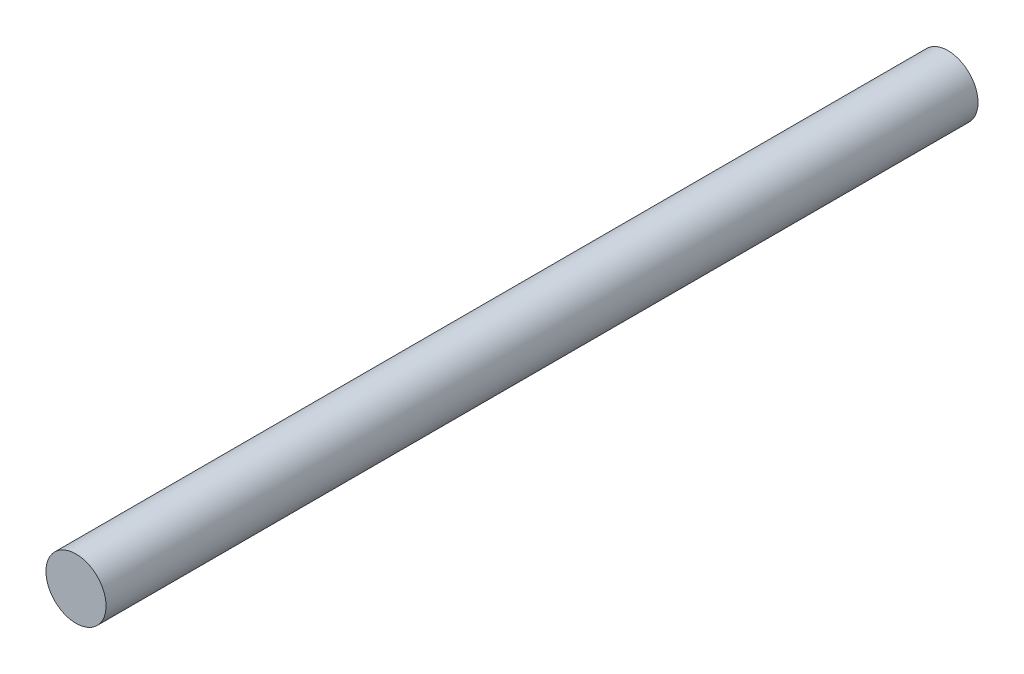
SolidWorks part; units mm, degrees
ref_plane "Front Plane" through (0, 0, 0) normal (0, 0, 1) x (1, 0, 0)
ref_plane "Top Plane" through (0, 0, 0) normal (0, 1, 0) x (1, 0, 0)
ref_plane "Right Plane" through (0, 0, 0) normal (1, 0, 0) x (0, 0, -1)
sketch "Sketch1" plane through (0, 0, 0) normal (0, 0, 1) x (1, 0, 0)
  circle A0 centre (0, 0) radius 5
  point P3 (0, 0)
  dimension "D1" = 10
extrude "Boss-Extrude1" add sketch "Sketch1" along normal mid plane 145
